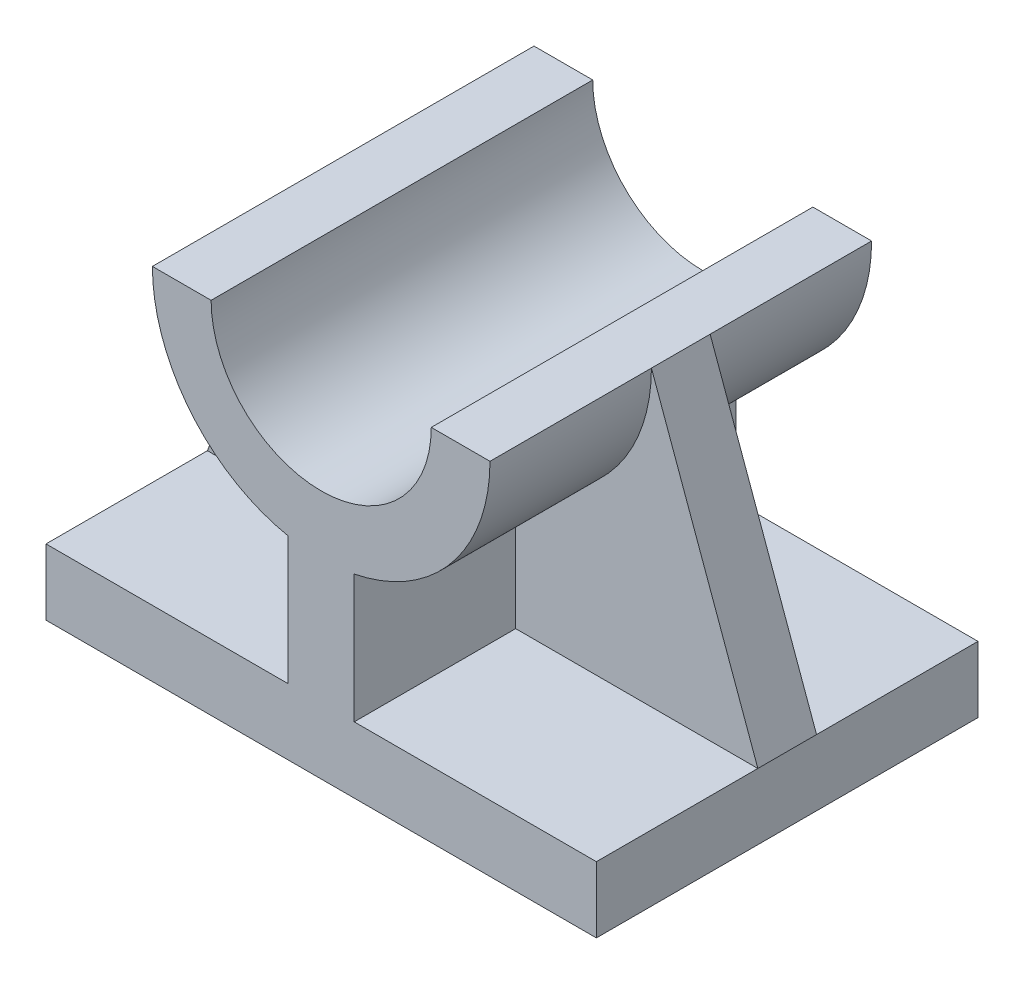
SolidWorks part; units mm, degrees
ref_plane "Front Plane" through (0, 0, 0) normal (0, 0, 1) x (1, 0, 0)
ref_plane "Top Plane" through (0, 0, 0) normal (0, 1, 0) x (1, 0, 0)
ref_plane "Right Plane" through (0, 0, 0) normal (1, 0, 0) x (0, 0, -1)
sketch "Sketch1" plane through (0, 0, 0) normal (0, 0, 1) x (1, 0, 0)
  line L0 (-584.2, 1130.3) -> (-381, 1130.3)
  line L1 (-952.5, 114.3) -> (-114.3, 114.3)
  line L2 (-952.5, 114.3) -> (-952.5, -114.3)
  line L3 (-952.5, -114.3) -> (952.5, -114.3)
  line L4 (952.5, 114.3) -> (952.5, -114.3)
  line L5 (-952.5, 114.3) -> (952.5, -114.3) construction
  line L6 (-952.5, -114.3) -> (952.5, 114.3) construction
  line L7 (381, 1130.3) -> (584.2, 1130.3)
  line L8 (0, 0) -> (0, 2536.0896) construction
  line L9 (-114.3, 114.3) -> (-114.3, 557.3906)
  line L10 (114.3, 114.3) -> (114.3, 557.3906)
  line L11 (114.3, 114.3) -> (952.5, 114.3)
  arc A0 (-381, 1130.3) -> (381, 1130.3) centre (0, 1130.3) ccw
  arc A1 (-584.2, 1130.3) -> (-114.3, 557.3906) centre (0, 1130.3) ccw
  arc A2 (114.3, 557.3906) -> (584.2, 1130.3) centre (0, 1130.3) ccw
  point P0 (0, 0)
  dimension "D3" = 762
  dimension "D4" = 1168.4
  dimension "D1" = 1905
  dimension "D2" = 228.6
  dimension "D5" = 1016
  dimension "D6" = 114.3
extrude "Boss-Extrude2" add sketch "Sketch1" along normal mid plane 1320.8
sketch "Sketch2" plane through (0, 0, 0) normal (0, 0, 1) x (1, 0, 0)
  line L0 (584.2, 1130.3) -> (952.5, 114.3)
rib "Rib1" sketch "Sketch2" sketch "Sketch2" thickness 203.2 extrusion direction parallel to sketch draft on no parameters "D1"=203.2
mirror "Mirror5" about plane through (0, 0, 0) normal (1, 0, 0) of "Rib1"
